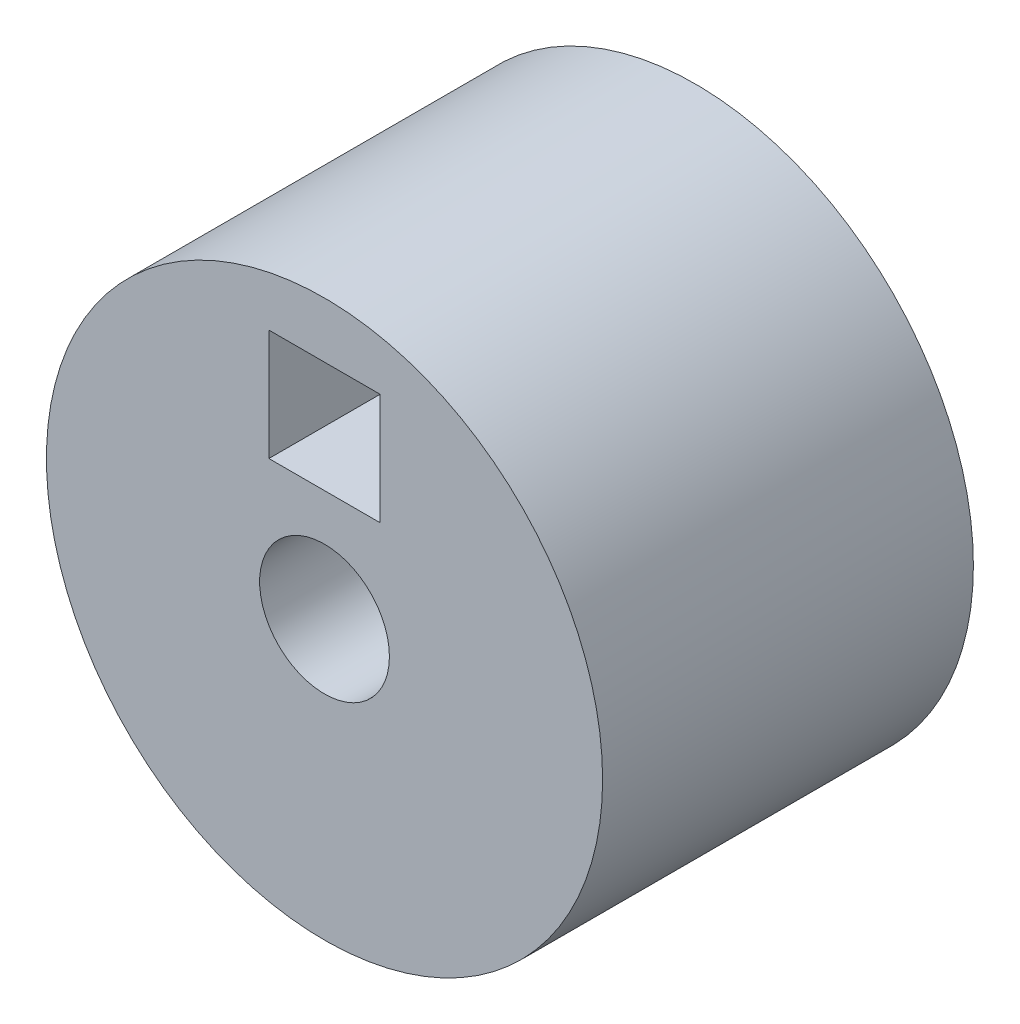
SolidWorks part; units mm, degrees
ref_plane "Front Plane" through (0, 0, 0) normal (0, 0, 1) x (1, 0, 0)
ref_plane "Top Plane" through (0, 0, 0) normal (0, 1, 0) x (1, 0, 0)
ref_plane "Right Plane" through (0, 0, 0) normal (1, 0, 0) x (0, 0, -1)
sketch "Sketch1" plane through (0, 0, 0) normal (0, 0, 1) x (1, 0, 0)
  circle A0 centre (0, 0) radius 7.5
  circle A1 centre (0, 0) radius 1.75
  dimension "D1" = 15
  dimension "D2" = 3.5
extrude "Boss-Extrude1" add sketch "Sketch1" along normal blind 10
sketch "Sketch2" plane through (0, 0, 0) normal (0, 0, -1) x (-1, 0, 0)
  line L0 (0, 0) -> (0, 7.5) construction
  line L2 (-1.5, 3) -> (1.5, 3)
  line L3 (-1.5, 3) -> (-1.5, 6)
  line L4 (-1.5, 6) -> (1.5, 6)
  line L5 (1.5, 3) -> (1.5, 6)
  line L6 (-1.5, 3) -> (1.5, 6) construction
  line L7 (-1.5, 6) -> (1.5, 3) construction
  circle A0 centre (0, 0) radius 4.5 construction
  circle A1 centre (0, 0) radius 7.5 construction
  point P3 (0, 4.5)
  dimension "D1" = 9
  dimension "D2" = 3
  dimension "D3" = 3
extrude "Cut-Extrude1" cut sketch "Sketch2" against normal through all
